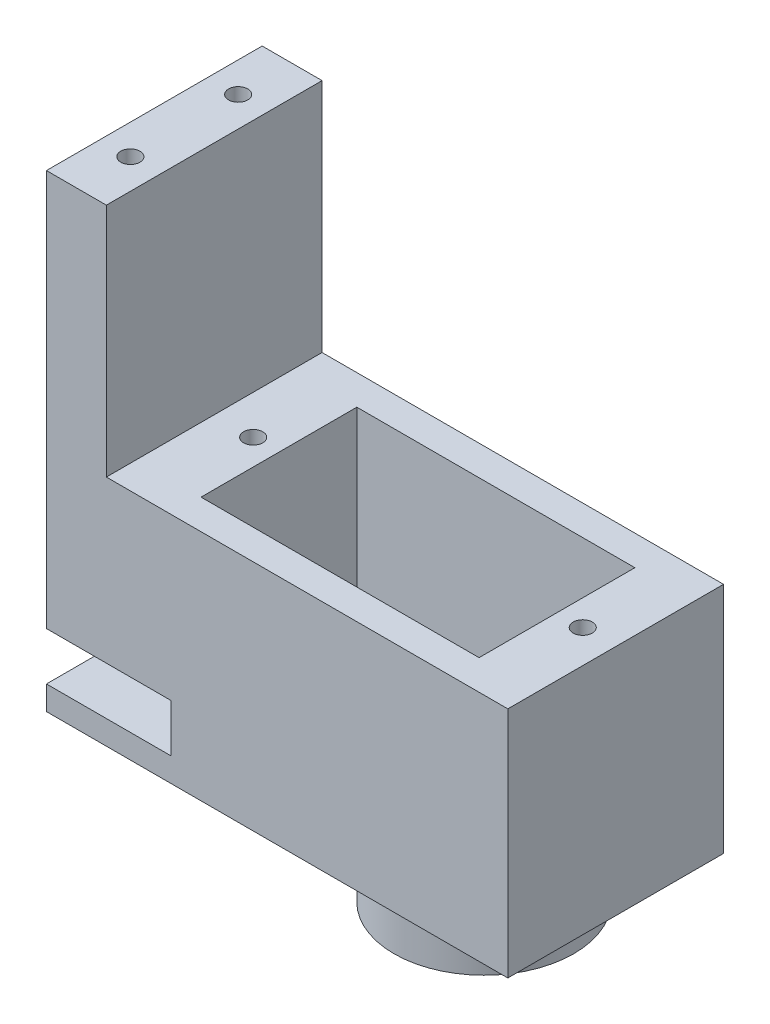
SolidWorks part; units mm, degrees
material "ABS"
ref_plane "Front Plane" through (0, 0, 0) normal (0, 0, 1) x (1, 0, 0)
ref_plane "Top Plane" through (0, 0, 0) normal (0, 1, 0) x (1, 0, 0)
ref_plane "Right Plane" through (0, 0, 0) normal (1, 0, 0) x (0, 0, -1)
sketch "Sketch1" plane through (0, 0, 0) normal (0, 0, 1) x (1, 0, 0)
  line L1 (-22, -14.3) -> (16.5, -14.3)
  line L2 (-22, -14.3) -> (-22, 5.15)
  line L3 (-22, 5.15) -> (16.5, 5.15)
  line L4 (16.5, -14.3) -> (16.5, 5.15)
extrude "Boss-Extrude1" add sketch "Sketch1" along normal mid plane 18
sketch "Sketch2" plane through (0, 0, 0) normal (0, 0, 1) x (1, 0, 0)
  line L1 (-22, 5.15) -> (-17, 5.15)
  line L2 (-22, 5.15) -> (-22, 24.8)
  line L3 (-22, 24.8) -> (-17, 24.8)
  line L4 (-17, 5.15) -> (-17, 24.8)
extrude "Boss-Extrude2" add sketch "Sketch2" along normal mid plane 18
ref_plane "Y-18_80" through (0, -18.8, 0) normal (0, 1, 0) x (1, 0, 0)
sketch "Sketch3" plane through (0, -18.8, 0) normal (0, 1, 0) x (1, 0, 0)
  circle A0 centre (5.5, 0) radius 7.5
extrude "Boss-Extrude3" add sketch "Sketch3" along normal blind 4.5
ref_plane "Y+5_15" through (0, 5.15, 0) normal (0, 1, 0) x (1, 0, 0)
sketch "Sketch4" plane through (0, 5.15, 0) normal (0, 1, 0) x (1, 0, 0)
  line L1 (-11.6, -6.5) -> (11.6, -6.5)
  line L2 (-11.6, -6.5) -> (-11.6, 6.5)
  line L3 (-11.6, 6.5) -> (11.6, 6.5)
  line L4 (11.6, -6.5) -> (11.6, 6.5)
extrude "Cut-Extrude1" cut sketch "Sketch4" against normal blind 17.45
sketch "Sketch5" plane through (0, -18.8, 0) normal (0, 1, 0) x (1, 0, 0)
  circle A0 centre (5.5, 0) radius 5
extrude "Cut-Extrude3" cut sketch "Sketch5" along normal blind 4
sketch "Sketch6" plane through (0, 0, 0) normal (0, 0, 1) x (1, 0, 0)
  line L0 (-22, 24.8) -> (-22, -14.3) construction
  line L1 (-22, -12.3) -> (-11.6, -12.3)
  line L2 (-22, -12.3) -> (-22, -8.3)
  line L3 (-22, -8.3) -> (-11.6, -8.3)
  line L4 (-11.6, -12.3) -> (-11.6, -8.3)
extrude "Cut-Extrude4" cut sketch "Sketch6" against normal through all and the other way through all
sketch "Sketch7" plane through (0, 5.15, 0) normal (0, 1, 0) x (1, 0, 0)
  circle A0 centre (-13.75, 0) radius 0.8
extrude "Cut-Extrude5" cut sketch "Sketch7" against normal blind 8
sketch "Sketch8" plane through (0, 5.15, 0) normal (0, 1, 0) x (1, 0, 0)
  circle A0 centre (13.75, 0) radius 0.8
extrude "Cut-Extrude6" cut sketch "Sketch8" against normal blind 8
ref_plane "Y+24_80" through (0, 24.8, 0) normal (0, 1, 0) x (1, 0, 0)
sketch "Sketch9" plane through (0, 24.8, 0) normal (0, 1, 0) x (1, 0, 0)
  circle A0 centre (-19.5, -4.5) radius 0.8
extrude "Cut-Extrude7" cut sketch "Sketch9" against normal blind 10
sketch "Sketch10" plane through (0, 24.8, 0) normal (0, 1, 0) x (1, 0, 0)
  circle A0 centre (-19.5, 4.5) radius 0.8
extrude "Cut-Extrude8" cut sketch "Sketch10" against normal blind 10
